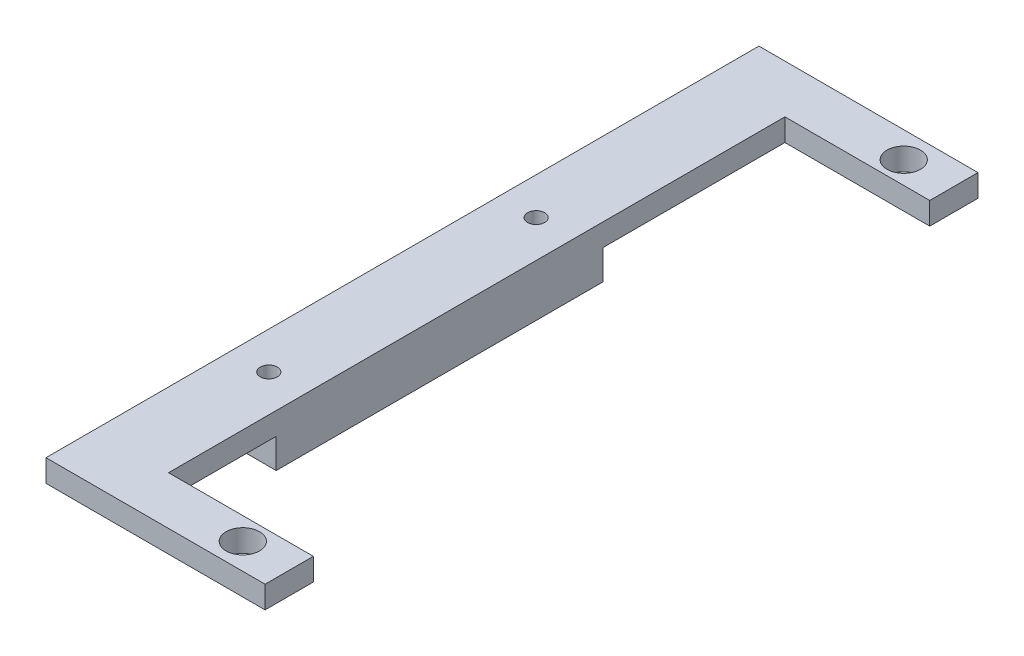
SolidWorks part; units mm, degrees
ref_plane "前视基准面" through (0, 0, 0) normal (0, 0, 1) x (1, 0, 0)
ref_plane "上视基准面" through (0, 0, 0) normal (0, 1, 0) x (1, 0, 0)
ref_plane "右视基准面" through (0, 0, 0) normal (1, 0, 0) x (0, 0, -1)
other "Configuration Table"
sketch "草图1" plane through (0, 0, 0) normal (0, 1, 0) x (1, 0, 0)
  line L1 (-5, 22) -> (5, 22)
  line L2 (-5, 22) -> (-5, -22)
  line L3 (-5, -22) -> (5, -22)
  line L4 (5, 22) -> (5, -22)
  line L5 (-5, 22) -> (5, -22) construction
  line L6 (-5, -22) -> (5, 22) construction
  circle A0 centre (0, -18) radius 1.15
  circle A1 centre (0, 18) radius 1.15
  point P0 (0, 0)
  point P10 (0, 0)
  point P13 (-93.8462, 41.1923)
  dimension "D2" = 2.3
  dimension "D3" = 2.3
  dimension "D1" = 10
  dimension "D4" = 18
  dimension "D5" = 18
  dimension "D6" = 44
extrude "凸台-拉伸1" add sketch "草图1" along normal blind 4
sketch "草图2" plane through (0, 4, 0) normal (0, 1, 0) x (1, 0, 0)
  line L0 (-5, -22) -> (-5, -43)
  line L1 (-5, -43) -> (24.5, -43)
  line L2 (24.5, -43) -> (24.5, -36.5)
  line L3 (24.5, -36.5) -> (5, -36.5)
  line L4 (5, -22) -> (5, 22)
  line L5 (5, 22) -> (-5, 22)
  line L6 (-5, 22) -> (-5, -22)
  line L7 (-5, -22) -> (5, -22)
  line L8 (5, -22) -> (5, 22)
  line L10 (-5, 22) -> (-5, -22)
  line L12 (5, -36.5) -> (5, -22)
  line L13 (-5, 22) -> (-5, 45.8963)
  line L14 (-999.4214, 5) -> (-5, 5) construction
  line L15 (5, 32) -> (5, -12)
  line L16 (-5, -12) -> (-5, 32)
  line L17 (24.5, 53) -> (24.5, 46.5)
  line L18 (-5, 53) -> (24.5, 53)
  line L19 (24.5, 46.5) -> (5, 46.5)
  line L20 (5, 46.5) -> (5, 32)
  line L21 (-5, 32) -> (-5, 53)
  line L22 (5, 5) -> (49000.5786, 5) construction
  circle A1 centre (0, -18) radius 1.15 construction
  circle A4 centre (18, -39.5) radius 2.25
  circle A5 centre (18, 49.5) radius 2.25
  circle M12 centre (0, -18) radius 1.15
  line M13 (5, -22) -> (5, 22)
  line M14 (5, 22) -> (-5, 22)
  line M15 (-5, 22) -> (-5, -22)
  line M16 (-5, -22) -> (5, -22)
  circle M17 centre (0, 18) radius 1.15
  dimension "D5" = 4.5
  dimension "D7" = 3
  dimension "D2" = 25
  dimension "D3" = 6.5
  dimension "D4" = 19.5
  dimension "D6" = 13
  dimension "D8" = 48
  dimension "D1" = 0
extrude "凸台-拉伸2" add sketch "草图2" along normal blind 3 contours L21 L13 L15 L20 L19 L17 L18 A5 M14 | L8 L10 M16 M13 M14 M15 M17 M12 | L3 L12 L0 L1 L2 A4 M16
